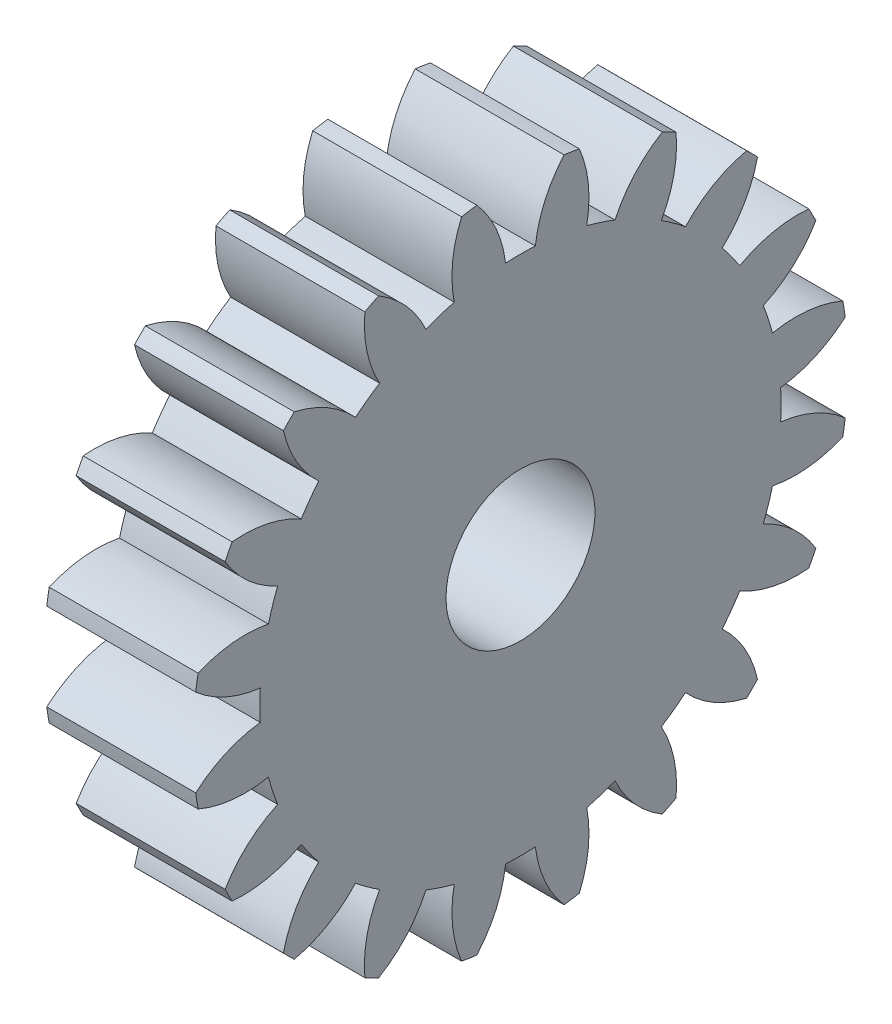
SolidWorks part; units mm, degrees
ref_plane "Plane1" through (0, 0, 0) normal (0, 0, 1) x (1, 0, 0)
ref_plane "Plane2" through (0, 0, 0) normal (0, 1, 0) x (1, 0, 0)
ref_plane "Plane3" through (0, 0, 0) normal (1, 0, 0) x (0, 0, -1)
sketch "HoldingSke" plane through (0, 0, 0) normal (0, 1, 0) x (1, 0, 0)
  line L0 (0, 0) -> (0.9397, -0.342)
  line L1 (-15, 0) -> (100, 0) construction
  line L2 (0, 0) -> (-2.1039, 2.3779)
  line L3 (0, 0) -> (-11.863, 4.5341)
  line L4 (0, 0) -> (8.1152, 2.9537)
  line L5 (0, 0) -> (-46.8476, -17.4728)
  line L6 (0, 0) -> (-4.1448, -2.7965)
  line L7 (-2.1039, 2.3779) -> (8.6586, 51.2059)
  line L8 (-76.2, 54.61) -> (-75.3, 54.61)
  line L9 (-71.009, 38.7566) -> (-53.1078, 45.2721)
  line L10 (-76.2, 71.12) -> (104.1128, 71.12)
  line L11 (0, 0) -> (-5, 0)
  line L12 (-76.2, 101.6) -> (-76.162, 101.6)
  line L13 (24.9733, 27.94) -> (52.9518, 28.4284)
  line L14 (24.9733, 27.94) -> (24.9743, 27.94)
  line L15 (24.9733, 27.94) -> (100.4006, 29.5858)
  line L16 (-63.627, -1) -> (-12.827, -1)
  circle A0 centre (0, 0) radius 2.5
  circle A1 centre (0, 0) radius 8.749
  circle A2 centre (0, 0) radius 37.5
  circle A3 centre (0, 0) radius 2.5
  dimension "MHD" = 17.498
  dimension "Hub_dia" = 75
  dimension "Bore" = 5
  dimension "MBD" = 5
  dimension "Num_teeth" = 20
  dimension "Pitch" = 1
  dimension "Overall_len" = 50
  dimension "Show_teeth" = 20
  dimension "Thickness" = 5
  dimension "OAL" = 50.0001
  dimension "T_dim" = 0.9
  dimension "Ap" = 20
  dimension "H" = 19.05
  dimension "Pitch_radius" = 180.3128
  dimension "Width" = 5
  dimension "Backlash" = 0.038
  dimension "Addendum_fac" = 1
  dimension "Dedendum_fac" = 1.25
  dimension "Clearance_fac" = 0.25
  dimension "Dedendum_add" = 0.001
  dimension "Module" = 1
sketch "BasProSke" plane through (0, 0, 0) normal (0, 1, 0) x (1, 0, 0)
  line L0 (-10, 0) -> (60, 0) construction
  line L1 (0, 0) -> (0, 11)
  line L2 (0, 0) -> (5, 0)
  line L3 (5, 0) -> (5, 11)
  line L4 (5, 11) -> (0, 11)
  dimension "Thickness" = 5
  dimension "Diameter" = 22
revolve "Base-Revolve" add sketch "BasProSke" angle 360 about L0
sketch "TooCutSke" plane through (0, 0, 0) normal (1, 0, 0) x (0, 0, -1)
  line L1 (0, 0) -> (0, 107) construction
  line L2 (0, 0) -> (-0.8511, 9.9637) construction
  line L3 (0, 0) -> (-3.1206, 19.7028) construction
  line L4 (-0.8511, 9.9637) -> (-1.5603, 9.8514) construction
  arc A0 (0.4999, 8.7347) -> (-0.4999, 8.7347) centre (0, 0) ccw
  arc A1 (1.4852, 10.9249) -> (-1.4852, 10.9249) centre (0, 0) ccw
  circle A2 centre (0, 0) radius 10 construction
  circle A3 centre (0, 0) radius 9.3969 construction
  arc A4 (-0.4999, 8.7347) -> (-1.4852, 10.9249) centre (-4.4722, 8.2645) ccw
  arc A5 (1.4852, 10.9249) -> (0.4999, 8.7347) centre (4.4722, 8.2645) ccw
  dimension "Root_dia" = 17.498
  dimension "Overcut_dia" = 22.0508
  dimension "Pitch_dia" = 20
  dimension "Base_dia" = 18.7939
  dimension "Flank_rad" = 4
  dimension "Half_ang" = 9
  dimension "Half_CT" = 0.7181
extrude "ToothCut" cut sketch "TooCutSke" along normal through all
fillet "Breaks" [suppressed] radius 0.02
fillet "RootFillets" [suppressed] radius 0.251
pattern_circular "TeethCuts" count 20 every 18 about axis through (-10, 0, 0) along (1, 0, 0) of "ToothCut", "RootFillets", "Breaks"
sketch "HubNeaOneSke" plane through (0, 0, 0) normal (-1, 0, 0) x (0, 0, 1)
  circle A0 centre (0, 0) radius 8.749
  dimension "Diameter" = 17.498
extrude "HubNearOne" [suppressed] add sketch "HubNeaOneSke" along normal blind 45.0001
sketch "HubNeaBotSke" plane through (0, 0, 0) normal (-1, 0, 0) x (0, 0, 1)
  circle A0 centre (0, 0) radius 8.749
  dimension "Diameter" = 17.498
extrude "HubNearBoth" [suppressed] add sketch "HubNeaBotSke" along normal blind 22.5
ref_plane "FarPln" through (5, 0, 0) normal (1, 0, 0) x (0, 0, -1)
sketch "HubFarSke" plane through (5, 0, 0) normal (1, 0, 0) x (0, 0, -1)
  circle A0 centre (0, 0) radius 8.749
  dimension "Diameter" = 17.498
extrude "HubFar" [suppressed] add sketch "HubFarSke" along normal blind 22.5
sketch "BorSke" plane through (0, 0, 0) normal (1, 0, 0) x (0, 0, -1)
  circle A0 centre (0, 0) radius 2.5
  dimension "Diameter" = 5
extrude "Bore" cut sketch "BorSke" along normal mid plane 100.0001
sketch "KeySke" plane through (0, 0, 0) normal (1, 0, 0) x (0, 0, -1)
  line L0 (-1, 0) -> (-1, 3.4)
  line L1 (-1, 3.4) -> (1, 3.4)
  line L2 (1, 3.4) -> (1, 0)
  line L3 (0, 0) -> (0, 34) construction
  line L4 (-1, 0) -> (1, 0)
  dimension "Offset" = 3.4
  dimension "Width" = 2
extrude "Keyway" [suppressed] cut sketch "KeySke" along normal mid plane 100.0001
pattern_circular "Keyway2" [suppressed] count 2 every 90 about axis through (-10, 0, 0) along (1, 0, 0)
equation "' \"Module@HoldingSke\" = 6.35"
equation "' \"Num_teeth@HoldingSke\" = 12"
equation "' \"Ap@HoldingSke\" =  20"
equation "' \"Ap@HoldingSke\" = 20"
equation "' \"Width@HoldingSke\" = 0.5 * 25.4"
equation "' \"Hub_dia@HoldingSke\"= 1 * 25.4"
equation "' \"Hub_dia@HoldingSke\" = 1 * 25.4"
equation "' \"Overall_len@HoldingSke\" = 1.0 * 25.4"
equation "' \"Bore@HoldingSke\" = 0.75 * 25.4"
equation "' \"T_dim@HoldingSke\" = 0.1 * 25.4"
equation "' \"Width@KeySke\" = 0.25 * 25.4"
equation "' \"Show_teeth@HoldingSke\" = 13"
equation "' \"Backlash@HoldingSke\" = 0.009 * 25.4"
equation "' \"Addendum_fac@HoldingSke\" = 1.0"
equation "' \"Dedendum_fac@HoldingSke\" = 1.25"
equation "' \"Dedendum_add@HoldingSke\" = 0.00005 * 25.4"
equation "' \"Clearance_fac@HoldingSke\" = 0.25"
equation "\"Pitch@HoldingSke\" = 1 / \"Module@HoldingSke\""
equation "\"Overcut_dia@TooCutSke\" = (\"Num_teeth@HoldingSke\" + 2 * \"Addendum_fac@HoldingSke\") / \"Pitch@HoldingSke\" + 0.002 * 25.4"
equation "\"Pitch_dia@TooCutSke\" = \"Num_teeth@HoldingSke\" / \"Pitch@HoldingSke\""
equation "\"Base_dia@TooCutSke\" = \"Num_teeth@HoldingSke\" / \"Pitch@HoldingSke\" * cos((\"Ap@HoldingSke\"  * 3.14159265 / 180))"
equation "\"Root_dia@TooCutSke\" = (\"Num_teeth@HoldingSke\" + 2) / \"Pitch@HoldingSke\" - 2 * (\"Addendum_fac@HoldingSke\" + \"Dedendum_fac@HoldingSke\") / \"Pitch@HoldingSke\" - \"Dedendum_add@HoldingSke\" * 2"
equation "\"Half_ang@TooCutSke\" = 180 / \"Num_teeth@HoldingSke\""
equation "\"Half_CT@TooCutSke\" = \"Num_teeth@HoldingSke\" / \"Pitch@HoldingSke\" * sin((3.14159265 / 2 / \"Num_teeth@HoldingSke\")) / 2 - 7 * \"Backlash@HoldingSke\" / 4"
equation "\"Flank_rad@TooCutSke\" = \"Num_teeth@HoldingSke\" / \"Pitch@HoldingSke\" / 5"
equation "\"Radius@RootFillets\" = \"Clearance_fac@HoldingSke\" / \"Pitch@HoldingSke\" + \"Dedendum_add@HoldingSke\""
equation "\"Break_rad@Breaks\" = 0.02 / \"Pitch@HoldingSke\""
equation "\"Thickness@HoldingSke\" = \"Width@HoldingSke\""
equation "\"OAL@HoldingSke\" = \"Thickness@HoldingSke\""
equation "\"MHD@HoldingSke\" = (\"Num_teeth@HoldingSke\" + 2) / \"Pitch@HoldingSke\" - 2 * (\"Addendum_fac@HoldingSke\" + \"Dedendum_fac@HoldingSke\")  / \"Pitch@HoldingSke\" - \"Dedendum_add@HoldingSke\" * 2"
equation "\"MBD@HoldingSke\" = (\"Num_teeth@HoldingSke\" + 2) / \"Pitch@HoldingSke\" - 2 * (\"Addendum_fac@HoldingSke\" + \"Dedendum_fac@HoldingSke\")  / \"Pitch@HoldingSke\" - \"Dedendum_add@HoldingSke\" * 2 - 0.002 * 25.4"
equation "\"MHD@HoldingSke\" = ((sgn( \"MHD@HoldingSke\" - \"Hub_dia@HoldingSke\" )-1)*( \"MHD@HoldingSke\" - \"Hub_dia@HoldingSke\" ))/-2+ \"Hub_dia@HoldingSke\""
equation "\"MBD@HoldingSke\" = ((sgn( \"MBD@HoldingSke\" - \"Bore@HoldingSke\" )-1)*( \"MBD@HoldingSke\" - \"Bore@HoldingSke\" ))/-2+ \"Bore@HoldingSke\""
equation "\"OAL@HoldingSke\" = ((sgn( \"OAL@HoldingSke\" - \"Overall_len@HoldingSke\" )+1)*( \"OAL@HoldingSke\" - \"Overall_len@HoldingSke\" ))/2 + \"Overall_len@HoldingSke\" + 0.000002 * 25.4"
equation "\"Num_teeth@TeethCuts\" = int( \"Show_teeth@HoldingSke\" ) + 1"
equation "\"Num_teeth@TeethCuts\" = ((sgn( \"Num_teeth@TeethCuts\" - \"Num_teeth@HoldingSke\" )-1)*( \"Num_teeth@TeethCuts\" - \"Num_teeth@HoldingSke\" ))/-2+ \"Num_teeth@HoldingSke\""
equation "\"Num_teeth@TeethCuts\" = ((sgn( \"Num_teeth@TeethCuts\" - 2.0)+1)*( \"Num_teeth@TeethCuts\" - 2.0))/2 +2.0"
equation "\"Angle@TeethCuts\" = 360.0 / \"Num_teeth@HoldingSke\""
equation "\"Diameter@BasProSke\" = (\"Num_teeth@HoldingSke\" + 2 * \"Addendum_fac@HoldingSke\") / \"Pitch@HoldingSke\""
equation "\"Thickness@BasProSke\"  = \"Thickness@HoldingSke\""
equation "' \"Fillet_rad@BasProSke\" =  \"Thickness@HoldingSke\" * 0.05"
equation "' \"Fillet_rad@BasProSke\" = \"Thickness@HoldingSke\" * 0.05"
equation "\"MHD@HoldingSke\" = ((sgn( \"MHD@HoldingSke\" - \"Root_dia@TooCutSke\" )-1)*( \"MHD@HoldingSke\" - \"Root_dia@TooCutSke\" ))/-2+ \"Root_dia@TooCutSke\""
equation "\"Diameter@HubNeaOneSke\" = \"MHD@HoldingSke\""
equation "\"Length@HubNearOne\" = \"OAL@HoldingSke\" - \"Thickness@BasProSke\""
equation "\"Diameter@HubNeaBotSke\" = \"MHD@HoldingSke\""
equation "\"Length@HubNearBoth\" = ( \"OAL@HoldingSke\" - \"Thickness@BasProSke\" ) / 2.0"
equation "\"Thickness@FarPln\" = \"Thickness@BasProSke\""
equation "\"Diameter@HubFarSke\" = \"MHD@HoldingSke\""
equation "\"Length@HubFar\" = ( \"OAL@HoldingSke\" - \"Thickness@BasProSke\" ) / 2.0"
equation "\"Diameter@BorSke\" = \"MBD@HoldingSke\""
equation "\"D1@Bore\" = \"OAL@HoldingSke\" * 2.0"
equation "\"D1@Keyway\" = \"OAL@HoldingSke\" * 2.0"
equation "\"Offset@KeySke\" = \"T_dim@HoldingSke\" + \"MBD@HoldingSke\" / 2.0"
